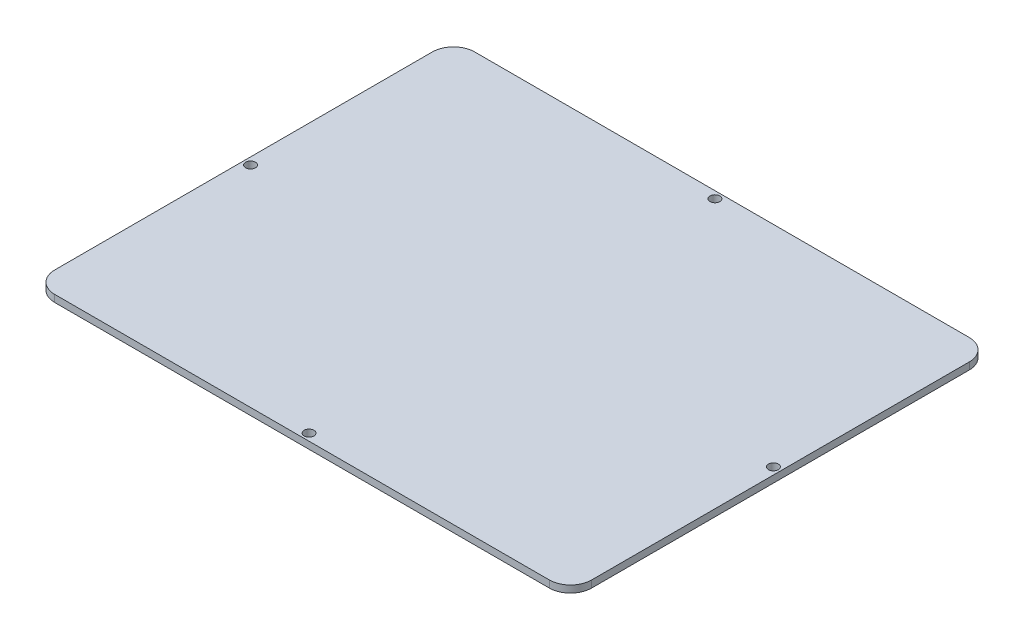
SolidWorks part; units mm, degrees
ref_plane "Front Plane" through (0, 0, 0) normal (0, 0, 1) x (1, 0, 0)
ref_plane "Top Plane" through (0, 0, 0) normal (0, 1, 0) x (1, 0, 0)
ref_plane "Right Plane" through (0, 0, 0) normal (1, 0, 0) x (0, 0, -1)
sketch "Sketch1" plane through (0, 0, 0) normal (0, 1, 0) x (1, 0, 0)
  line L27 (76.2, -53.6) -> (76.2, 53.6)
  line L28 (-70.2, -59.6) -> (70.2, -59.6)
  line L29 (70.2, 59.6) -> (-70.2, 59.6)
  line L30 (-76.2, 53.6) -> (-76.2, -53.6)
  line L31 (76.2, -53.6) -> (76.2, 53.6)
  line L32 (-70.2, -59.6) -> (70.2, -59.6)
  line L33 (70.2, 59.6) -> (-70.2, 59.6)
  line L34 (-76.2, 53.6) -> (-76.2, -53.6)
  circle A21 centre (0, -57.6) radius 1.4 construction
  circle A22 centre (74.2, 0) radius 1.4 construction
  circle A23 centre (0, 57.6) radius 1.4 construction
  circle A24 centre (-74.2, 0) radius 1.4 construction
  arc A25 (76.2, 53.6) -> (70.2, 59.6) centre (70.2, 53.6) ccw
  arc A26 (70.2, -59.6) -> (76.2, -53.6) centre (70.2, -53.6) ccw
  arc A27 (-76.2, -53.6) -> (-70.2, -59.6) centre (-70.2, -53.6) ccw
  arc A28 (-70.2, 59.6) -> (-76.2, 53.6) centre (-70.2, 53.6) ccw
  arc A29 (76.2, 53.6) -> (70.2, 59.6) centre (70.2, 53.6) ccw
  arc A30 (70.2, -59.6) -> (76.2, -53.6) centre (70.2, -53.6) ccw
  arc A31 (-76.2, -53.6) -> (-70.2, -59.6) centre (-70.2, -53.6) ccw
  arc A32 (-70.2, 59.6) -> (-76.2, 53.6) centre (-70.2, 53.6) ccw
  circle A33 centre (0, -57.6) radius 1.4
  circle A34 centre (74.2, 0) radius 1.4
  circle A35 centre (0, 57.6) radius 1.4
  circle A36 centre (-74.2, 0) radius 1.4
  dimension "D1" = 0.5
extrude "Boss-Extrude1" add sketch "Sketch1" along normal blind 2
